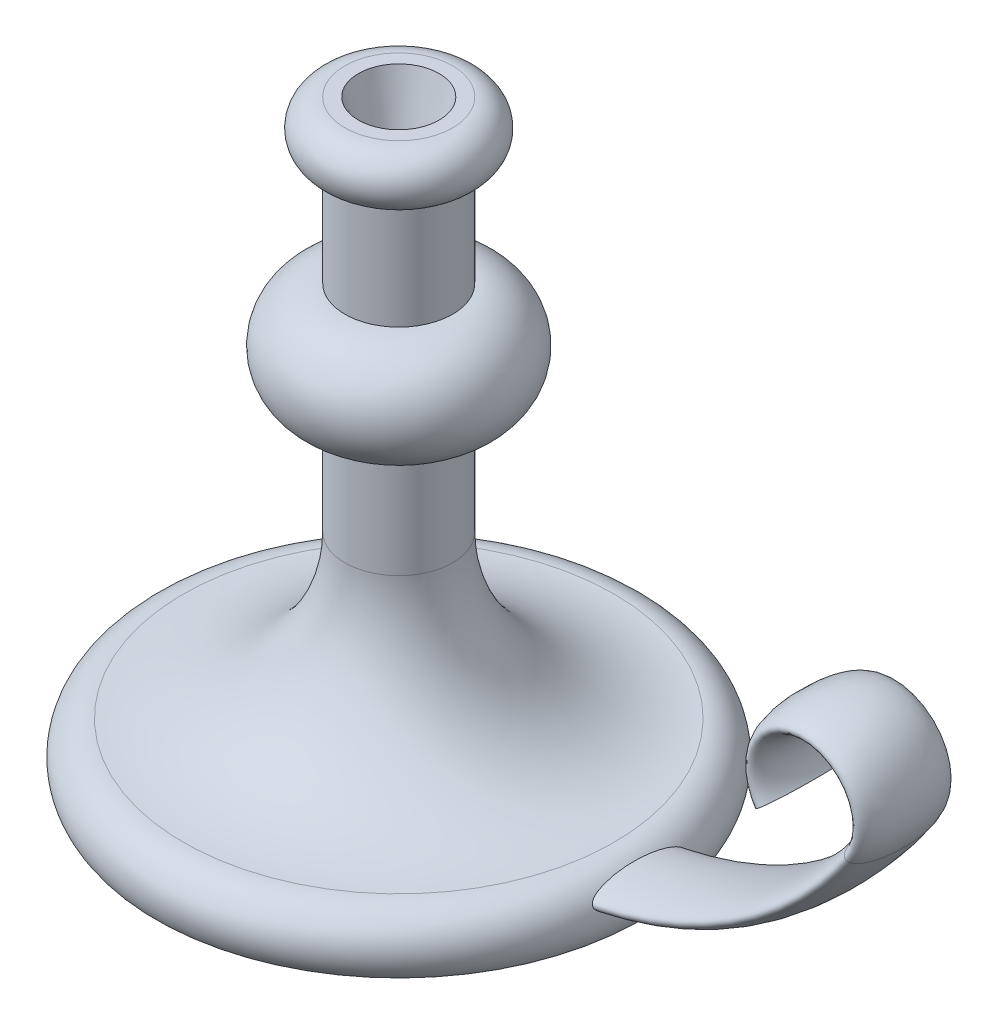
SolidWorks part; units mm, degrees
ref_plane "Front" through (0, 0, 0) normal (0, 0, 1) x (1, 0, 0)
ref_plane "Top" through (0, 0, 0) normal (0, 1, 0) x (1, 0, 0)
ref_plane "Right" through (0, 0, 0) normal (1, 0, 0) x (0, 0, -1)
sketch "Sketch1" plane through (0, 0, 0) normal (0, 0, 1) x (1, 0, 0)
  line L0 (0, 0) -> (0, 220)
  line L1 (0, 220) -> (20, 220)
  line L2 (0, 0) -> (90, 0)
  line L3 (20, 200) -> (20, 160)
  line L4 (20, 120) -> (20, 80)
  arc A0 (20, 220) -> (20, 200) centre (20, 210) cw
  arc A1 (20, 160) -> (20, 120) centre (20, 140) cw
  arc A2 (20, 80) -> (80, 20) centre (80, 80) ccw
  arc A3 (80, 20) -> (90, 0) centre (80, 7.5) cw
  dimension "D4" = 10
  dimension "D5" = 20
  dimension "D7" = 60
  dimension "D8" = 12.5
  dimension "D1" = 220
  dimension "D2" = 90
  dimension "D3" = 20
  dimension "D6" = 40
revolve "Revolve1" add sketch "Sketch1" angle 360 about L0
sketch "Sketch2" plane through (0, 0, 0) normal (0, 0, 1) x (1, 0, 0)
  line L0 (0, 10) -> (60, 10)
  line L1 (0, 227.4356) -> (0, 175.1288) construction
  line L2 (0, 200) -> (0, 160) construction
  line L3 (-90, 0) -> (90, 0) construction
  arc A0 (60, 10) -> (183.5921, 75) centre (60, 160) ccw
  arc A1 (183.5921, 75) -> (150.6342, 75) centre (167.1131, 86.3333) ccw
  dimension "D2" = 150
  dimension "D4" = 20
  dimension "D1" = 60
  dimension "D3" = 65
  dimension "D5" = 10
sketch "Sketch3" plane through (0, 0, 0) normal (1, 0, 0) x (0, 0, -1)
  ellipse E0 centre (0, 10) end of major axis (17.5, 10) minor radius 5
  dimension "D1" = 10
  dimension "D2" = 35
sweep "Sweep1" add profiles "Sketch3" path "Sketch2"
sketch "Sketch5" plane through (0, 220, 0) normal (0, 1, 0) x (1, 0, 0)
  circle A0 centre (0, 0) radius 15
  dimension "D1" = 30
extrude "Cut-Extrude1" cut sketch "Sketch5" against normal blind 25 draft 15
